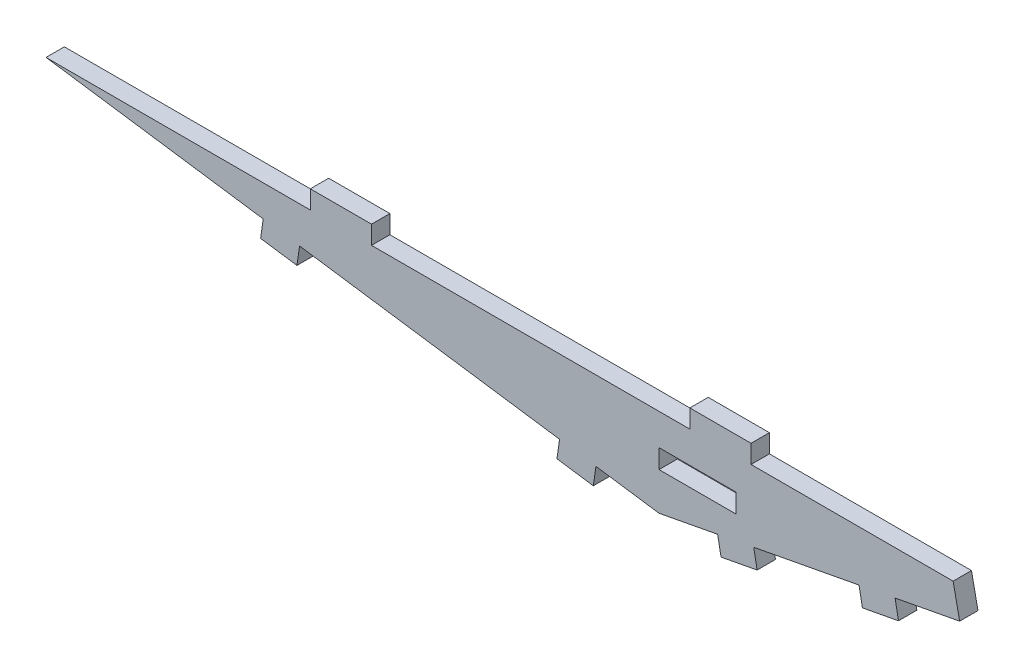
SolidWorks part; units mm, degrees
ref_plane "Front Plane" through (0, 0, 0) normal (0, 0, 1) x (1, 0, 0)
ref_plane "Top Plane" through (0, 0, 0) normal (0, 1, 0) x (1, 0, 0)
ref_plane "Right Plane" through (0, 0, 0) normal (1, 0, 0) x (0, 0, -1)
sketch "Sketch1" plane through (0, 0, 0) normal (0, 0, 1) x (1, 0, 0)
  line L0 (-23.4032, -4.1332) -> (-28.7616, -5.1463)
  line L1 (-48.356, -8.8509) -> (-53.5934, -8.0967)
  line L3 (-23.9439, -1.524) -> (-40.7177, -1.524)
  line L4 (-43.4902, -7.9309) -> (-48.356, -8.8509)
  line L5 (-31.7566, -5.7125) -> (-40.4953, -7.3647)
  line L6 (-31.7566, -5.7125) -> (-31.4734, -7.21)
  line L7 (-43.4902, -7.9309) -> (-43.2071, -9.4284)
  line L8 (-28.7616, -5.1463) -> (-28.4785, -6.6437)
  line L9 (-40.4953, -7.3647) -> (-40.2122, -8.8622)
  line L10 (-56.6102, -7.6623) -> (-78.1919, -4.5547)
  line L11 (-31.4734, -7.21) -> (-28.4785, -6.6437)
  line L12 (-81.2088, -4.1203) -> (-99.2391, -1.524)
  line L13 (-40.7177, -1.524) -> (-40.7177, 0)
  line L14 (-81.2088, -4.1203) -> (-81.426, -5.6287)
  line L15 (-56.6102, -7.6623) -> (-56.8274, -9.1707)
  line L16 (-78.1919, -4.5547) -> (-78.4091, -6.0631)
  line L17 (-53.5934, -8.0967) -> (-53.8106, -9.6051)
  line L18 (-23.4032, -4.1332) -> (-23.9439, -1.524)
  line L19 (-81.426, -5.6287) -> (-78.4091, -6.0631)
  line L20 (-43.2071, -9.4284) -> (-40.2122, -8.8622)
  line L21 (-56.8274, -9.1707) -> (-53.8106, -9.6051)
  line L22 (-40.7177, 0) -> (-45.7977, 0)
  line L23 (-45.7977, 0) -> (-45.7977, -1.524)
  line L24 (-45.7977, 0) -> (-45.7977, -1.524) construction
  line L25 (-72.2201, -1.524) -> (-72.2201, 0)
  line L26 (-72.2201, 0) -> (-77.3001, 0)
  line L27 (-77.3001, 0) -> (-77.3001, -1.524)
  line L28 (-77.3001, -1.524) -> (-99.2391, -1.524)
  line L29 (-45.7977, -1.524) -> (-72.2201, -1.524)
  line L30 (-41.9577, -5.7125) -> (-48.356, -5.7125)
  line L31 (-41.9577, -5.7125) -> (-41.9577, -4.1332)
  line L32 (-41.9577, -4.1332) -> (-48.356, -4.1332)
  line L33 (-48.356, -5.7125) -> (-48.356, -4.1332)
extrude "Boss-Extrude1" add sketch "Sketch1" against normal blind 1.524
